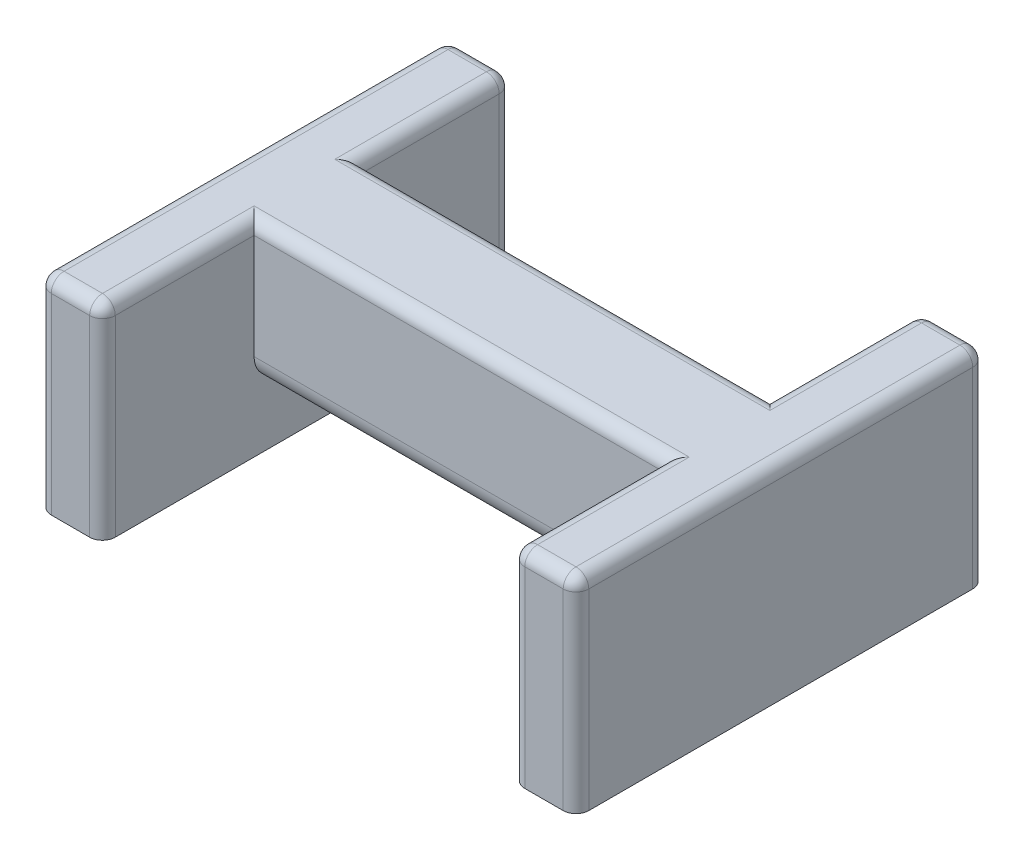
SolidWorks part; units mm, degrees
ref_plane "Front Plane" through (0, 0, 0) normal (0, 0, 1) x (1, 0, 0)
ref_plane "Top Plane" through (0, 0, 0) normal (0, 1, 0) x (1, 0, 0)
ref_plane "Right Plane" through (0, 0, 0) normal (1, 0, 0) x (0, 0, -1)
sketch "Sketch1" plane through (0, 0, 0) normal (0, 1, 0) x (1, 0, 0)
  line L1 (-16, -4.15) -> (16, -4.15)
  line L2 (-16, -4.15) -> (-16, 4.15)
  line L3 (-16, 4.15) -> (16, 4.15)
  line L4 (16, -4.15) -> (16, 4.15)
  line L5 (-16, -4.15) -> (16, 4.15) construction
  line L6 (-16, 4.15) -> (16, -4.15) construction
  point P0 (0, 0)
  dimension "D1" = 32
  dimension "D2" = 8.3
extrude "Boss-Extrude1" add sketch "Sketch1" along normal blind 11.2
sketch "Sketch2" plane through (16, 0, 0) normal (1, 0, 0) x (0, 0, -1)
  line L0 (-16, 11.2) -> (16, 11.2)
  line L2 (-4.15, 11.2) -> (4.15, 11.2) construction
  line L3 (-4.15, 11.2) -> (4.15, 11.2)
  line L4 (-16, 11.2) -> (-16, -4.8)
  line L5 (16, 11.2) -> (16, -4.8)
  line L6 (16, -4.8) -> (-16, -4.8)
  point P3 (0, 11.2)
  point P6 (0, 11.2)
  line M3 (-4.15, 0) -> (4.15, 0)
  line M4 (4.15, 0) -> (4.15, 11.2)
  line M5 (4.15, 11.2) -> (-4.15, 11.2)
  line M6 (-4.15, 11.2) -> (-4.15, 0)
  dimension "D1" = 32
  dimension "D2" = 16
extrude "Boss-Extrude2" add sketch "Sketch2" along normal blind 5 contours L6 L5 L0 L4 M4 M3 M6 | M6 M3 M4 M5
sketch "Sketch3" plane through (-16, 0, 0) normal (-1, 0, 0) x (0, 0, 1)
  line L0 (4.15, 11.2) -> (-4.15, 11.2) construction
  line L1 (4.15, 11.2) -> (-4.15, 11.2)
  line L4 (16, 11.2) -> (-16, 11.2)
  line L5 (-16, 11.2) -> (-16, -4.8)
  line L6 (-16, -4.8) -> (16, -4.8)
  line L7 (16, -4.8) -> (16, 11.2)
  line L8 (16, 11.2) -> (-16, 11.2)
  line L9 (-16, 11.2) -> (-16, -4.8)
  line L10 (-16, -4.8) -> (16, -4.8)
  line L11 (16, -4.8) -> (16, 11.2)
  line M5 (-4.15, 0) -> (4.15, 0)
  line M6 (4.15, 0) -> (4.15, 11.2)
  line M7 (4.15, 11.2) -> (-4.15, 11.2)
  line M8 (-4.15, 11.2) -> (-4.15, 0)
  dimension "D1" = 0
extrude "Boss-Extrude3" add sketch "Sketch3" along normal blind 5 contours L10 L11 L8 L9 M6 M5 M8 | M8 M5 M6 M7
fillet "Fillet1" radius 1 20 edges at (-21, 11.2, 0) (16, 11.2, -10.075) (0, 11.2, -4.15) (-16, 11.2, -10.075) (-16, 11.2, 10.075) (0, 11.2, 4.15) (16, 11.2, 10.075) (18.5, 11.2, 16) (21, 11.2, 0) (18.5, 11.2, -16) (21, 3.2, -16) (16, 3.2, -16) (-16, 3.2, -16) (-21, 3.2, -16) (21, 3.2, 16) (16, 3.2, 16) (-16, 3.2, 16) (-21, 3.2, 16) (-18.5, 11.2, -16) (-18.5, 11.2, 16)
fillet "Fillet2" radius 2 2 edges at (0, 0, -4.15) (0, 0, 4.15)
sketch "Sketch4" plane through (0, -4.8, 0) normal (0, -1, 0) x (1, 0, 0)
  line L0 (-18.5, 16) -> (-18.5, -16) construction
  line L1 (0, 16) -> (0, -16) construction
  line L4 (-20, -16) -> (-17, -16)
  line L5 (-16, -15) -> (-16, 15)
  line L6 (-17, 16) -> (-20, 16)
  line L7 (-21, 15) -> (-21, -15)
  line L8 (-20, -16) -> (-17, -16)
  line L9 (-16, -15) -> (-16, 15)
  line L10 (-17, 16) -> (-20, 16)
  line L11 (-21, 15) -> (-21, -15)
  circle A0 centre (-18.5, 0) radius 1.4
  circle A1 centre (18.5, 0) radius 1.4
  arc A4 (-17, -16) -> (-16, -15) centre (-17, -15) ccw
  arc A5 (-16, 15) -> (-17, 16) centre (-17, 15) ccw
  arc A6 (-20, 16) -> (-21, 15) centre (-20, 15) ccw
  arc A7 (-21, -15) -> (-20, -16) centre (-20, -15) ccw
  arc A8 (-17, -16) -> (-16, -15) centre (-17, -15) ccw
  arc A9 (-16, 15) -> (-17, 16) centre (-17, 15) ccw
  arc A10 (-20, 16) -> (-21, 15) centre (-20, 15) ccw
  arc A11 (-21, -15) -> (-20, -16) centre (-20, -15) ccw
  dimension "D2" = 2.8
  dimension "D1" = 0
extrude "Cut-Extrude1" cut sketch "Sketch4" against normal blind 8 contours A0 | A1
